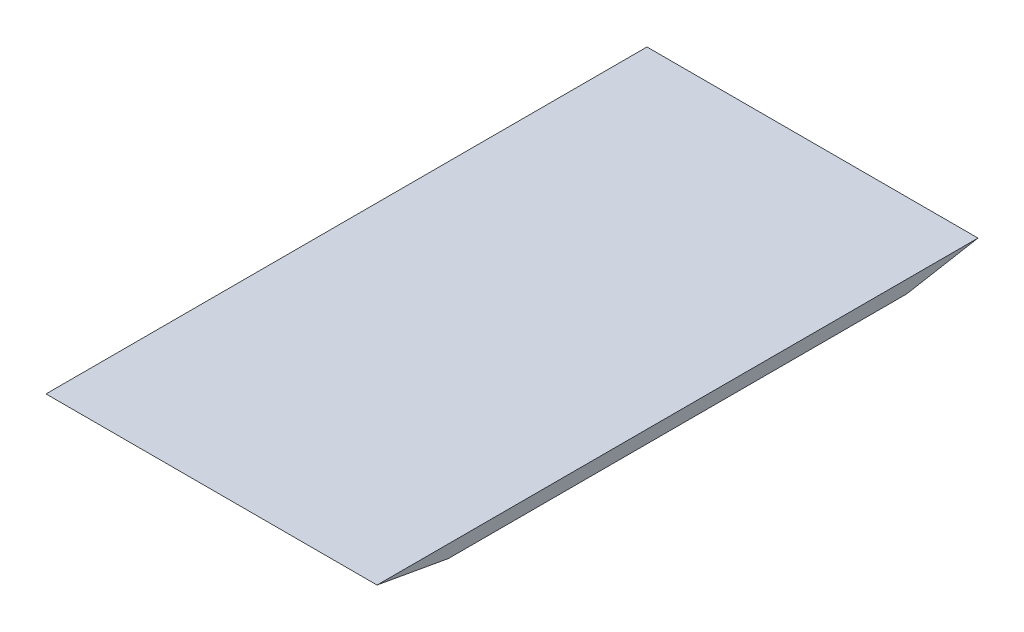
SolidWorks part; units mm, degrees
ref_plane "Front Plane" through (0, 0, 0) normal (0, 0, 1) x (1, 0, 0)
ref_plane "Top Plane" through (0, 0, 0) normal (0, 1, 0) x (1, 0, 0)
ref_plane "Right Plane" through (0, 0, 0) normal (1, 0, 0) x (0, 0, -1)
sketch "Sketch1" plane through (0, 0, 0) normal (1, 0, 0) x (0, 0, -1)
  line L0 (0, 0) -> (236, 0)
  line L1 (236, 0) -> (208, -5)
  line L2 (208, -5) -> (28, -5)
  line L3 (28, -5) -> (0, 0)
  point P3 (118, 0)
  dimension "D1" = 180
  dimension "D2" = 28
  dimension "D3" = 28
  dimension "D4" = 5
extrude "Boss-Extrude1" add sketch "Sketch1" along normal blind 130
